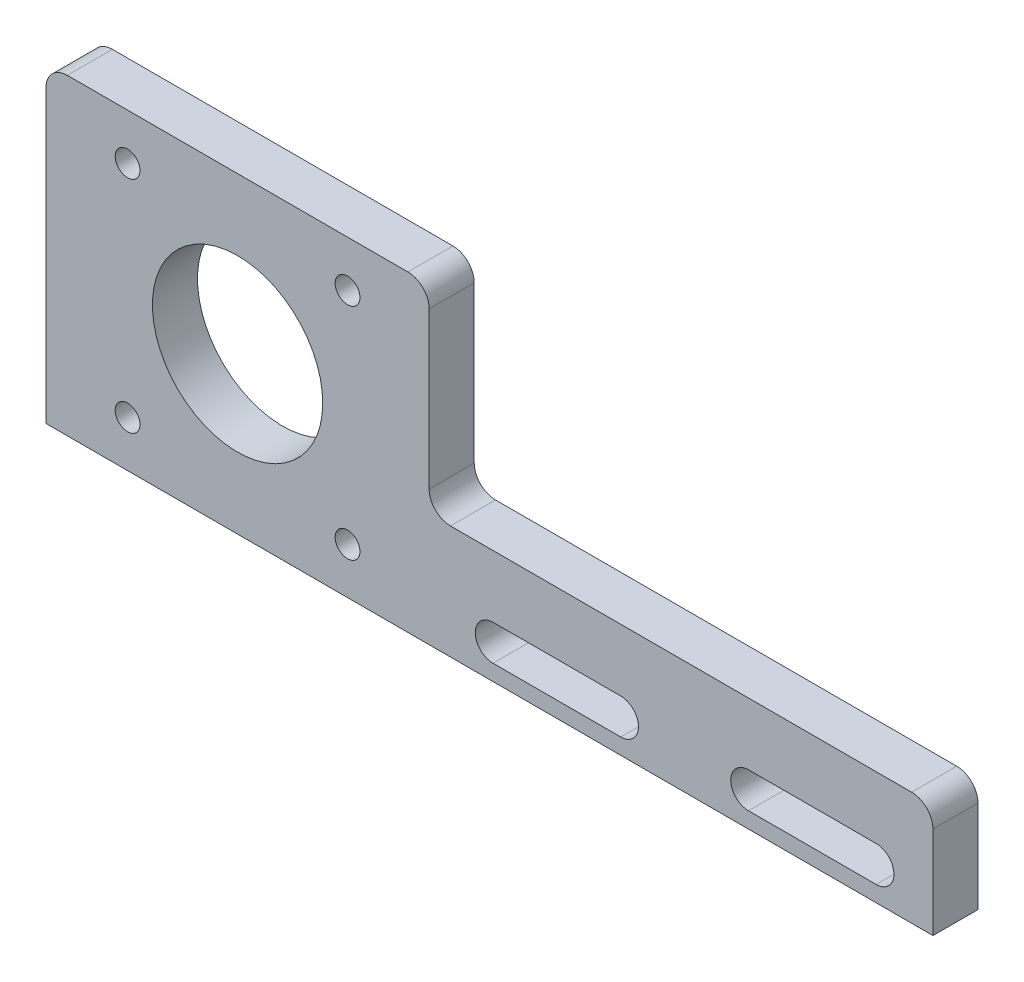
SolidWorks part; units mm, degrees
ref_plane "Alzado" through (0, 0, 0) normal (0, 0, 1) x (1, 0, 0)
ref_plane "Planta" through (0, 0, 0) normal (0, 1, 0) x (1, 0, 0)
ref_plane "Vista lateral" through (0, 0, 0) normal (1, 0, 0) x (0, 0, -1)
sketch "Croquis2" plane through (0, 0, 0) normal (0, 0, 1) x (1, 0, 0)
  line L1 (-0.5, -8.5) -> (-0.5, 19.7961) construction
  line L4 (-27.5, -30.5) -> (97.5, -30.5)
  line L5 (-27.5, -30.5) -> (-27.5, 13.5)
  line L6 (-27.5, 13.5) -> (26.5, 13.5)
  line L8 (26.5, 13.5) -> (26.5, -14.5)
  line L9 (-27.5, -25.76) -> (97.5, -25.76) construction
  line L11 (-0.5, -53.0697) -> (-0.5, 13.5) construction
  line L12 (-0.5, -8.5) -> (34.1547, -8.5) construction
  line L13 (-0.5, -8.5) -> (-27.5, -8.5) construction
  line L14 (62.5, -14.5) -> (62.5, -30.5) construction
  line L16 (71.5, -25.76) -> (89.5, -25.76) construction
  line L17 (71.5, -23.26) -> (89.5, -23.26)
  line L18 (71.5, -28.26) -> (89.5, -28.26)
  line L19 (97.5, -14.5) -> (26.5, -14.5)
  line L20 (53.5, -25.76) -> (35.5, -25.76) construction
  line L23 (97.5, -30.5) -> (97.5, -14.5)
  line L24 (53.5, -23.26) -> (35.5, -23.26)
  line L25 (53.5, -28.26) -> (35.5, -28.26)
  line L26 (-16, -24) -> (-16, 7) construction
  line L27 (-16, 7) -> (15, 7) construction
  line L28 (15, 7) -> (15, -24) construction
  line L29 (15, -24) -> (-16, -24) construction
  circle A0 centre (-16, 7) radius 1.75
  arc A1 (71.5, -23.26) -> (71.5, -28.26) centre (71.5, -25.76) ccw
  arc A2 (89.5, -28.26) -> (89.5, -23.26) centre (89.5, -25.76) ccw
  circle A3 centre (15, 7) radius 1.75
  circle A4 centre (15, -24) radius 1.75
  circle A5 centre (-16, -24) radius 1.75
  arc A6 (53.5, -23.26) -> (53.5, -28.26) centre (53.5, -25.76) cw
  arc A7 (35.5, -28.26) -> (35.5, -23.26) centre (35.5, -25.76) cw
  circle A8 centre (-0.5, -8.5) radius 12
  point P34 (80.5, -25.76)
  point P48 (44.5, -25.76)
  dimension "D1" = 3.5
  dimension "D2" = 24
  dimension "D8" = 15.5
  dimension "D12" = 8
  dimension "D14" = 9
  dimension "D18" = 27
  dimension "D3" = 54
  dimension "D4" = 44
  dimension "D5" = 4.74
  dimension "D6" = 125
  dimension "D7" = 16
  dimension "D10" = 31
  dimension "D11" = 31
  dimension "D13" = 18
  dimension "D15" = 11.5
  dimension "D16" = 6.5
  dimension "D17" = 5
extrude "Saliente-Extruir1" add sketch "Croquis2" along normal blind 6.35
fillet "Redondeo1" radius 3 4 edges at (97.5, -14.5, 3.175) (26.5, -14.5, 3.175) (26.5, 13.5, 3.175) (-27.5, 13.5, 3.175)
